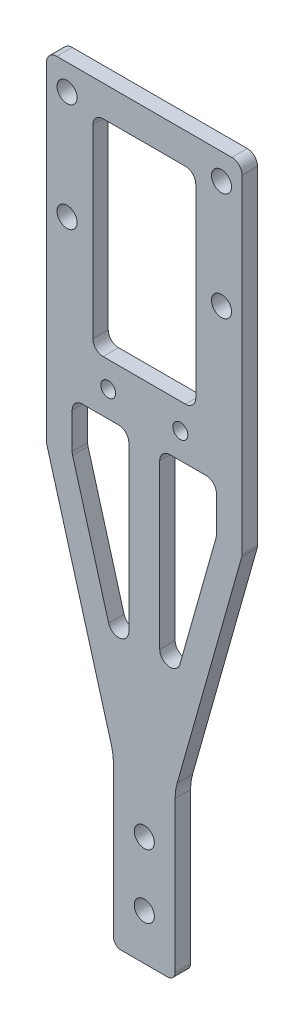
SolidWorks part; units mm, degrees
material "Thornel Mat VMA"
ref_plane "前视基准面" through (0, 0, 0) normal (0, 0, 1) x (1, 0, 0)
ref_plane "上视基准面" through (0, 0, 0) normal (0, 1, 0) x (1, 0, 0)
ref_plane "右视基准面" through (0, 0, 0) normal (1, 0, 0) x (0, 0, -1)
sketch "草图1" plane through (0, 0, 0) normal (0, 0, 1) x (1, 0, 0)
  line L0 (0, 0) -> (0, 66)
  line L1 (0, 66) -> (38, 66)
  line L2 (38, 66) -> (38, 0)
  line L4 (25, -78.1) -> (13, -78.1)
  line L6 (4, 40) -> (34, 40) construction
  line L7 (4, 40) -> (4, 61) construction
  line L8 (4, 61) -> (34, 61) construction
  line L9 (34, 61) -> (34, 40) construction
  line L10 (19, 66) -> (19, 61) construction
  line L11 (0, 0) -> (38, 0) construction
  line L12 (19, -56.8) -> (19, -69.2) construction
  line L16 (0, 0) -> (13, -45.9276)
  line L17 (13, -45.9276) -> (13, -78.1)
  line L18 (38, 0) -> (25, -45.9276)
  line L19 (25, -45.9276) -> (25, -78.1)
  line L20 (19, -69.2) -> (19, -78.1) construction
  line L21 (19, -63) -> (19, 20) construction
  circle A0 centre (4, 40) radius 1.95
  circle A1 centre (34, 40) radius 1.95
  circle A2 centre (4, 61) radius 1.95
  circle A3 centre (34, 61) radius 1.95
  circle A4 centre (19, -56.8) radius 1.95
  circle A6 centre (19, -69.2) radius 1.95
  dimension "D1" = 3.9
  dimension "D2" = 3.9
  dimension "D5" = 3.9
  dimension "D6" = 3.9
  dimension "D10" = 3.9
  dimension "D11" = 15.1
  dimension "D12" = 3.9
  dimension "D13" = 12.4
  dimension "D14" = 20
  dimension "D16" = 83
  dimension "D3" = 30
  dimension "D4" = 21
  dimension "D7" = 38
  dimension "D8" = 40
  dimension "D9" = 5
  dimension "D15" = 12
extrude "凸台-拉伸1" add sketch "草图1" along normal blind 3
sketch "草图2" plane through (0, 0, 3) normal (0, 0, 1) x (1, 0, 0)
  line L3 (19, 15.9452) -> (19, 60) construction
  line L7 (38, 66) -> (0, 66) construction
  line L8 (5, 10) -> (16, 10)
  line L9 (9, 60) -> (29, 60)
  line L10 (9, 60) -> (9, 20)
  line L11 (9, 20) -> (29, 20)
  line L12 (29, 60) -> (29, 20)
  line L13 (16, 10) -> (16, -38.1678)
  line L15 (22, 10) -> (22, -38.1678)
  line L17 (33, 10) -> (22, 10)
  line L18 (5, 10) -> (5, 0.694)
  line L19 (5, 0.694) -> (16, -38.1678)
  line L20 (33, 10) -> (33, 0.694)
  line L21 (33, 0.694) -> (22, -38.1678)
  line L22 (25, -45.9276) -> (38, 0) construction
  line L23 (0, 0) -> (13, -45.9276) construction
  line L24 (0, 66) -> (0, 0) construction
  line L25 (38, 0) -> (38, 66) construction
  circle A0 centre (4, 40) radius 1.95 construction
  circle A1 centre (12, 15) radius 1.45
  circle A2 centre (26, 15) radius 1.45
  point P7 (19, 60)
  dimension "D1" = 51
  dimension "D4" = 2.9
  dimension "D5" = 51
  dimension "D7" = 2.9
  dimension "D8" = 7
  dimension "D3" = 5
  dimension "D6" = 7
  dimension "D10" = 5
  dimension "D11" = 5
  dimension "D2" = 6
  dimension "D9" = 5
  dimension "D12" = 3
  dimension "D13" = 3
  dimension "D14" = 5
  dimension "D15" = 5
  dimension "D16" = 5
  dimension "D17" = 5
extrude "切除-拉伸1" cut sketch "草图2" against normal blind 10
fillet "圆角1" radius 1.5 4 edges at (0, 0, 1.5) (38, 0, 1.5) (25, -78.1, 1.5) (13, -78.1, 1.5)
fillet "圆角2" radius 10 2 edges at (13, -45.9276, 1.5) (25, -45.9276, 1.5)
fillet "圆角3" radius 2 14 edges at (9, 60, 1.5) (29, 60, 1.5) (29, 20, 1.5) (9, 20, 1.5) (0, 66, 1.5) (38, 66, 1.5) (16, -38.1678, 1.5) (22, -38.1678, 1.5) (22, 10, 1.5) (33, 0.694, 1.5) (33, 10, 1.5) (16, 10, 1.5) (5, 10, 1.5) (5, 0.694, 1.5)
